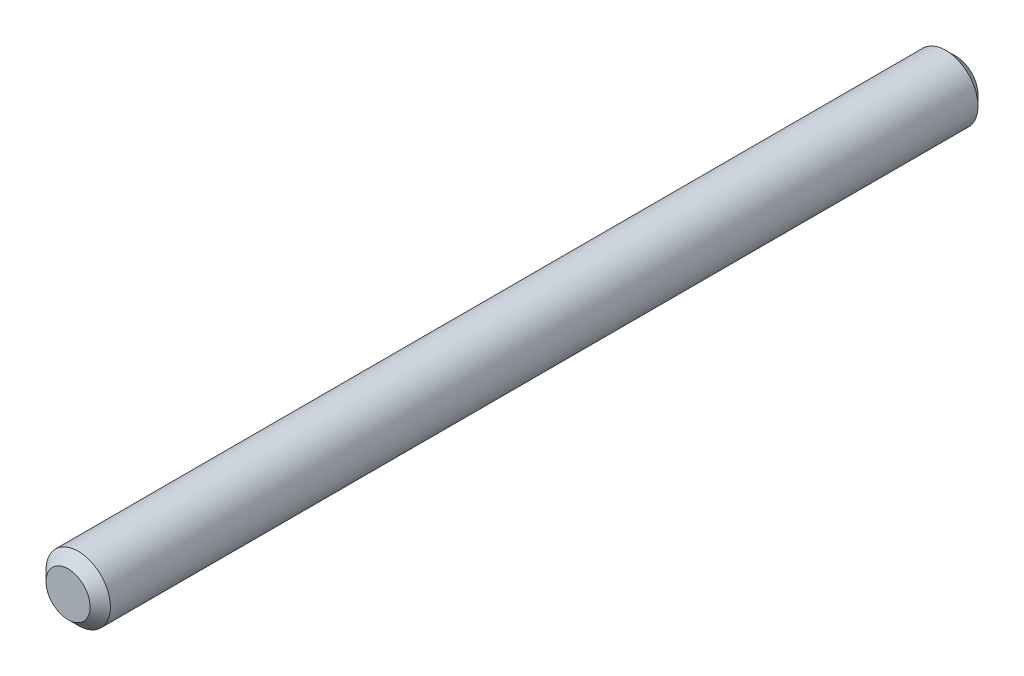
SolidWorks part; units mm, degrees
material "AISI 1020"
ref_plane "Front Plane" through (0, 0, 0) normal (0, 0, 1) x (1, 0, 0)
ref_plane "Top Plane" through (0, 0, 0) normal (0, 1, 0) x (1, 0, 0)
ref_plane "Right Plane" through (0, 0, 0) normal (1, 0, 0) x (0, 0, -1)
sketch "Sketch1" plane through (0, 0, 0) normal (0, 0, 1) x (1, 0, 0)
  circle A0 centre (0, 0) radius 3.175
  dimension "D1" = 6.35
extrude "Boss-Extrude1" add sketch "Sketch1" against normal blind 87.5
cosmetic thread "Cosmetic Thread1" parameters "D2"=4.8387
chamfer "Chamfer1" distance 1 angle 45 2 edges at (3.175, 0, -87.5) (3.175, 0, 0)
